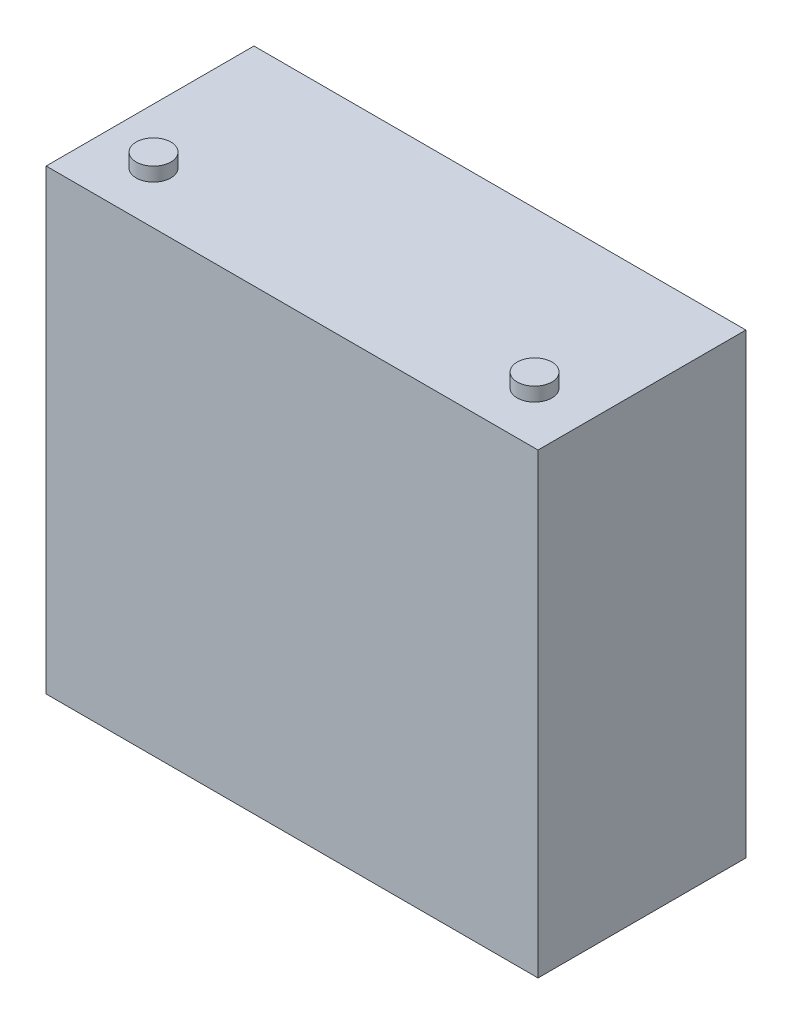
SolidWorks part; units mm, degrees
material "Nylon 101"
ref_plane "Front Plane" through (0, 0, 0) normal (0, 0, 1) x (1, 0, 0)
ref_plane "Top Plane" through (0, 0, 0) normal (0, 1, 0) x (1, 0, 0)
ref_plane "Right Plane" through (0, 0, 0) normal (1, 0, 0) x (0, 0, -1)
sketch "Sketch1" plane through (0, 0, 0) normal (0, 1, 0) x (1, 0, 0)
  line L1 (-90.17, -38.1) -> (90.17, -38.1)
  line L2 (-90.17, -38.1) -> (-90.17, 38.1)
  line L3 (-90.17, 38.1) -> (90.17, 38.1)
  line L4 (90.17, -38.1) -> (90.17, 38.1)
  line L5 (-90.17, -38.1) -> (90.17, 38.1) construction
  line L6 (-90.17, 38.1) -> (90.17, -38.1) construction
  point P0 (0, 0)
  dimension "D1" = 76.2
  dimension "D2" = 180.34
extrude "Boss-Extrude1" add sketch "Sketch1" along normal blind 167.64
sketch "Sketch2" plane through (0, 167.64, 0) normal (0, 1, 0) x (1, 0, 0)
  line L0 (0, 38.1) -> (0, -19.05) construction
  line L1 (90.17, 38.1) -> (-90.17, 38.1) construction
  line L2 (-69.85, -19.05) -> (69.85, -19.05) construction
  circle A0 centre (-69.85, -19.05) radius 6.35
  circle A1 centre (69.85, -19.05) radius 6.35
  point P8 (0, -19.05)
  dimension "D2" = 12.7
  dimension "D3" = 12.7
  dimension "D1" = 139.7
extrude "Boss-Extrude2" add sketch "Sketch2" along normal blind 5.08
